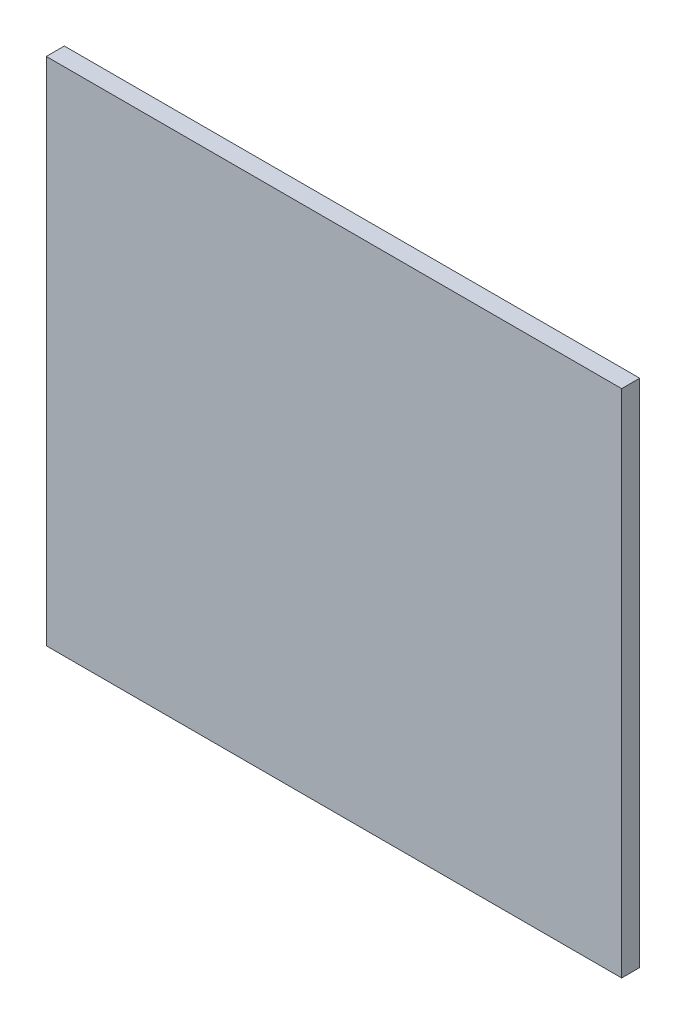
SolidWorks part; units mm, degrees
material "Гипс"
ref_plane "Спереди" through (0, 0, 0) normal (0, 0, 1) x (1, 0, 0)
ref_plane "Сверху" through (0, 0, 0) normal (0, 1, 0) x (1, 0, 0)
ref_plane "Справа" through (0, 0, 0) normal (1, 0, 0) x (0, 0, -1)
sketch "Эскиз1" plane through (0, 0, 0) normal (0, 0, 1) x (1, 0, 0)
  line L0 (-900, -353.5) -> (-400, -353.5) construction
  line L1 (-400, 0) -> (-1.5, 0)
  line L2 (-400, 0) -> (-400, -353.5)
  line L3 (-400, -353.5) -> (-1.5, -353.5)
  line L4 (-1.5, 0) -> (-1.5, -353.5)
extrude "Бобышка-Вытянуть1" add sketch "Эскиз1" against normal blind 12.5
